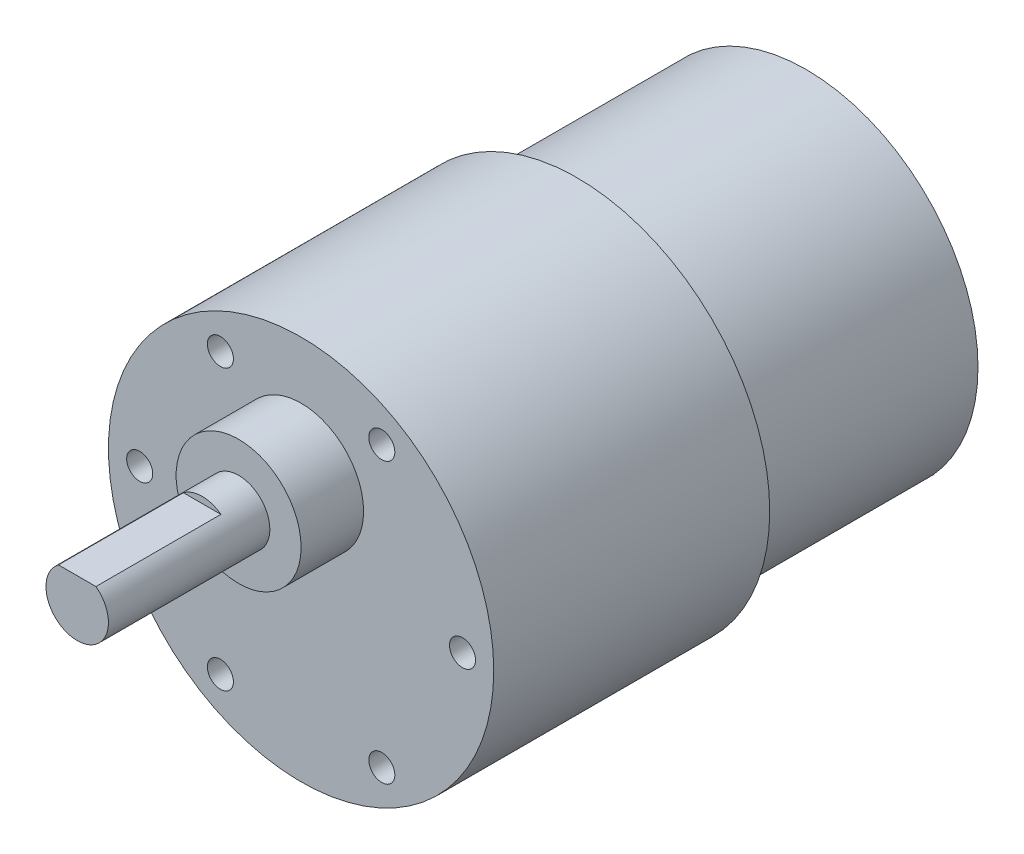
SolidWorks part; units mm, degrees
ref_plane "前视基准面" through (0, 0, 0) normal (0, 0, 1) x (1, 0, 0)
ref_plane "上视基准面" through (0, 0, 0) normal (0, 1, 0) x (1, 0, 0)
ref_plane "右视基准面" through (0, 0, 0) normal (1, 0, 0) x (0, 0, -1)
sketch "草图1" plane through (0, 0, 0) normal (0, 0, 1) x (1, 0, 0)
  circle A0 centre (0, 0) radius 18.5
  dimension "D1" = 37
extrude "凸台-拉伸1" add sketch "草图1" along normal blind 26.5
sketch "草图2" plane through (0, 0, 26.5) normal (0, 0, 1) x (1, 0, 0)
  circle A0 centre (0, 7) radius 6
  dimension "D1" = 7
  dimension "D2" = 12
extrude "凸台-拉伸2" add sketch "草图2" along normal blind 6
sketch "草图3" plane through (0, 0, 32.5) normal (0, 0, 1) x (1, 0, 0)
  circle A0 centre (0, 7) radius 3
  dimension "D1" = 6
extrude "凸台-拉伸3" add sketch "草图3" along normal blind 15.5
sketch "草图4" plane through (0, 0, 48) normal (0, 0, 1) x (1, 0, 0)
  line L1 (-2.923, 11.192) -> (3.522, 11.192)
  line L2 (-2.923, 11.192) -> (-2.923, 9.4)
  line L3 (-2.923, 9.4) -> (3.522, 9.4)
  line L4 (3.522, 11.192) -> (3.522, 9.4)
  circle A0 centre (0, 7) radius 3 construction
  dimension "D1" = 2.4
extrude "切除-拉伸1" cut sketch "草图4" against normal blind 12
sketch "草图5" plane through (0, 0, 0) normal (0, 0, -1) x (-1, 0, 0)
  circle A0 centre (0, 0) radius 16.5
  dimension "D1" = 33
extrude "凸台-拉伸4" add sketch "草图5" along normal blind 22
sketch "草图6" plane through (0, 0, 26.5) normal (0, 0, 1) x (1, 0, 0)
  line L0 (0, 0) -> (0, 18.5) construction
  line L1 (0, 0) -> (-7.75, 13.4234) construction
  circle A0 centre (0, 0) radius 15.5 construction
  circle A1 centre (-7.75, 13.4234) radius 1.5
  circle A2 centre (0, 0) radius 18.5 construction
  circle A3 centre (7.75, 13.4234) radius 1.5
  circle A4 centre (15.5, 0) radius 1.5
  circle A5 centre (7.75, -13.4234) radius 1.5
  circle A6 centre (-7.75, -13.4234) radius 1.5
  circle A7 centre (-15.5, 0) radius 1.5
  point P22 (0, 0)
  dimension "D1" = 31
  dimension "D3" = 3
  dimension "D2" = 30
  dimension "D4" = 6
hole_wizard "M3 螺纹孔1" positions "3D草图1" profile "草图7" tap size "M3" standard "GB"
sketch3d "3D草图1"
  point P0 (-7.75, 13.4234, 26.5)
  point P3 (7.75, 13.4234, 26.5)
  point P6 (15.5, 0, 26.5)
  point P9 (7.75, -13.4234, 26.5)
  point P12 (-7.75, -13.4234, 26.5)
  point P15 (-15.5, 0, 26.5)
sketch "草图7" plane through (-7.75, 13.4234, 26.5) normal (1, 0, 0) x (0, -1, 0)
  line L0 (0, 0) -> (0, 8.2511)
  line L1 (0, 8.2511) -> (1.25, 7.5)
  line L2 (1.25, 7.5) -> (1.25, 0)
  line L5 (1.25, 0) -> (0, 0)
  line L10 (0, 8.2511) -> (-1.25, 7.5) construction
  line L11 (0, -6.35) -> (0, 107.95) construction
  dimension "螺纹孔钻头直径" = 2.5
  dimension "螺纹孔钻头深度" = 7.5
  dimension "导头角度" = 118
cosmetic thread "孔螺蚊线1" parameters "D1"=6, "D2"=3
cosmetic thread "孔螺蚊线2" parameters "D1"=6, "D2"=3
cosmetic thread "孔螺蚊线3" parameters "D1"=6, "D2"=3
cosmetic thread "孔螺蚊线4" parameters "D1"=6, "D2"=3
cosmetic thread "孔螺蚊线5" parameters "D1"=6, "D2"=3
cosmetic thread "孔螺蚊线6" parameters "D1"=6, "D2"=3
sketch "草图8" plane through (0, 0, -22) normal (0, 0, -1) x (-1, 0, 0)
  circle A0 centre (0, 0) radius 14
  dimension "D1" = 28
extrude "凸台-拉伸5" add sketch "草图8" along normal blind 4.5
ref_plane "基准面1" through (0, 0, -24.5) normal (0, 0, -1) x (-1, 0, 0)
sketch "草图9" plane through (0, 0, -24.5) normal (0, 0, -1) x (-1, 0, 0)
  circle A0 centre (0, 0) radius 14
  circle A1 centre (0, 0) radius 8
  dimension "D1" = 16
extrude "切除-拉伸2" cut sketch "草图9" against normal up to surface (2.5 mm away) up to face at (-14, 0, -22)
sketch "草图10" plane through (0, 0, -26.5) normal (0, 0, -1) x (-1, 0, 0)
  circle A0 centre (0, 0) radius 14
  circle A1 centre (0, 0) radius 9.6574
extrude "切除-拉伸3" cut sketch "草图10" against normal blind 3
